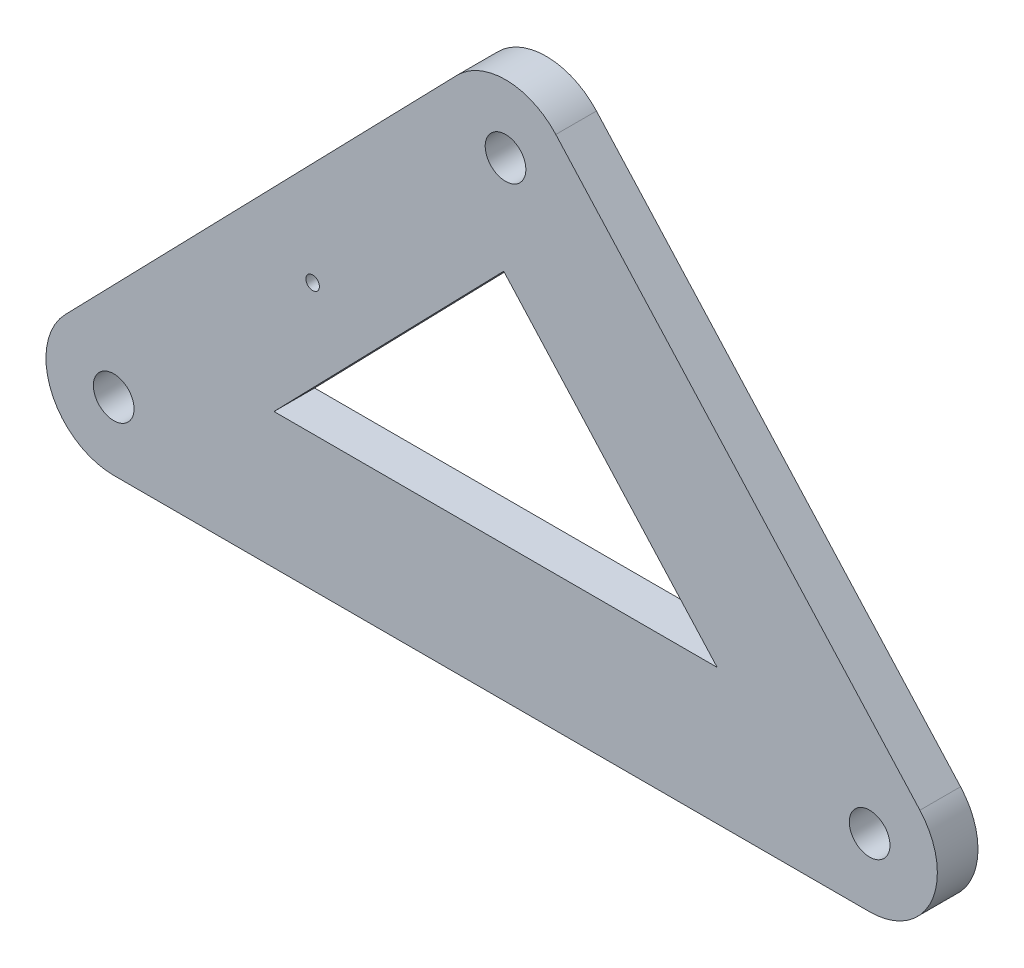
SolidWorks part; units mm, degrees
material "Acrylic (Medium-high impact)"
ref_plane "Front Plane" through (0, 0, 0) normal (0, 0, 1) x (1, 0, 0)
ref_plane "Top Plane" through (0, 0, 0) normal (0, 1, 0) x (1, 0, 0)
ref_plane "Right Plane" through (0, 0, 0) normal (1, 0, 0) x (0, 0, -1)
sketch "Sketch1" plane through (0, 0, 0) normal (0, 0, 1) x (1, 0, 0)
  line L3 (-3.5856, 3.4848) -> (25.3381, 33.245)
  line L4 (32.6344, 33.1114) -> (59.5108, 3.3512)
  line L5 (55.8, -5) -> (0, -5)
  line L6 (11.8318, 5) -> (28.7898, 22.4484)
  line L7 (28.7898, 22.4484) -> (44.5473, 5)
  line L8 (44.5473, 5) -> (11.8318, 5)
  circle A0 centre (28.9237, 29.7602) radius 1.5
  circle A1 centre (0, 0) radius 1.5
  circle A2 centre (55.8, 0) radius 1.5
  arc A3 (32.6344, 33.1114) -> (25.3381, 33.245) centre (28.9237, 29.7602) ccw
  arc A4 (0, -5) -> (-3.5856, 3.4848) centre (0, 0) cw
  arc A5 (55.8, -5) -> (59.5108, 3.3512) centre (55.8, 0) ccw
  dimension "D6" = 3
  dimension "D7" = 3
  dimension "D8" = 3
  dimension "D4" = 5
  dimension "D5" = 5
  dimension "D9" = 5
  dimension "D1" = 41.5
  dimension "D2" = 40.1
  dimension "D3" = 55.8
extrude "Boss-Extrude1" add sketch "Sketch1" along normal blind 3
sketch "Sketch2" plane through (0, 0, 3) normal (0, 0, 1) x (1, 0, 0)
  circle A0 centre (14.6844, 14.6605) radius 0.5
  circle A1 centre (0, 0) radius 1.5 construction
  dimension "D1" = 1
  dimension "D2" = 20.75
extrude "Cut-Extrude1" cut sketch "Sketch2" against normal through all
